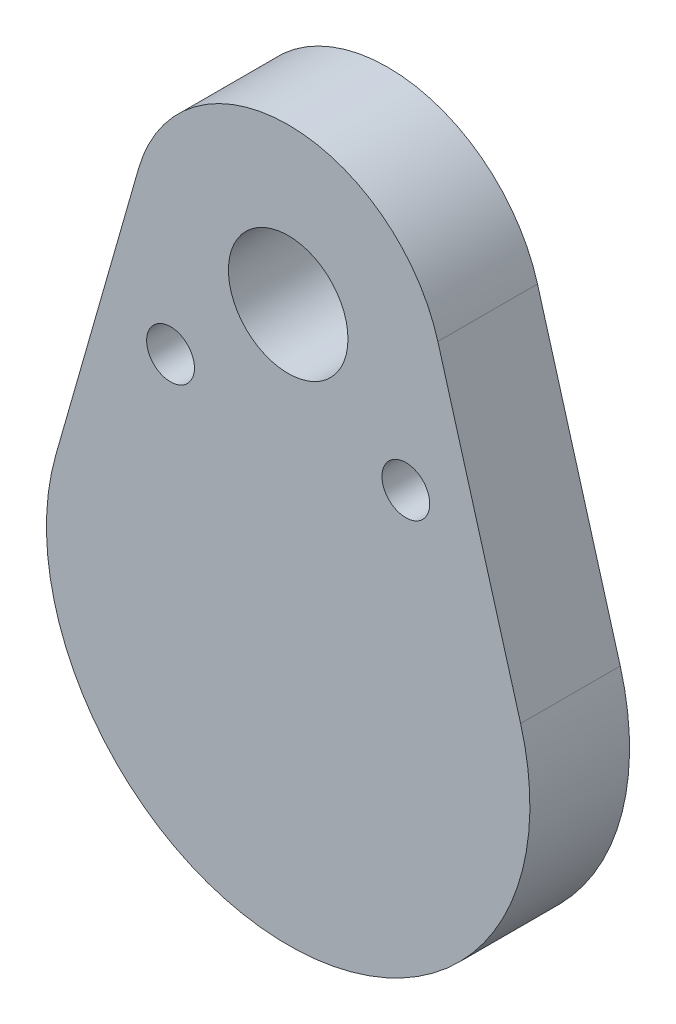
SolidWorks part; units mm, degrees
ref_plane "Plan de face" through (0, 0, 0) normal (0, 0, 1) x (1, 0, 0)
ref_plane "Plan de dessus" through (0, 0, 0) normal (0, 1, 0) x (1, 0, 0)
ref_plane "Plan de droite" through (0, 0, 0) normal (1, 0, 0) x (0, 0, -1)
sketch "Esquisse1" plane through (0, 0, 0) normal (0, 0, 1) x (1, 0, 0)
  line L0 (7.5117, 17.8612) -> (11.6646, 3.3348)
  line L1 (-7.5117, 17.8612) -> (-11.6646, 3.3348)
  line L2 (0, 15.7137) -> (0, 0) construction
  circle A0 centre (0, 0) radius 5.1299 construction
  circle A1 centre (0, 0) radius 12.1319 construction
  circle A2 centre (0, 15.7137) radius 3
  circle A3 centre (0, 15.7137) radius 7.8126 construction
  arc A4 (-7.5117, 17.8612) -> (7.5117, 17.8612) centre (0, 15.7137) cw
  arc A5 (11.6646, 3.3348) -> (-11.6646, 3.3348) centre (0, 0) cw
  circle A6 centre (5.9048, 10.598) radius 1.2
  circle A7 centre (-5.9048, 10.598) radius 1.2
  dimension "D1" = 2.4
  dimension "D2" = 2.4
  dimension "D3" = 6
extrude "Boss.-Extru.1" add sketch "Esquisse1" along normal blind 5
